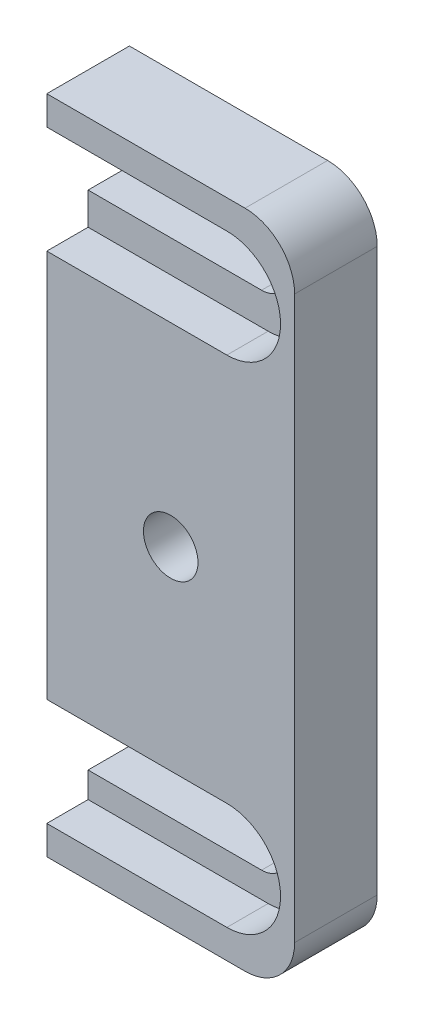
SolidWorks part; units mm, degrees
material "AISI 316 Annealed Stainless Steel Bar (SS)"
ref_plane "Front Plane" through (0, 0, 0) normal (0, 0, 1) x (1, 0, 0)
ref_plane "Top Plane" through (0, 0, 0) normal (0, 1, 0) x (1, 0, 0)
ref_plane "Right Plane" through (0, 0, 0) normal (1, 0, 0) x (0, 0, -1)
sketch "Sketch1" plane through (0, 0, 0) normal (0, 0, 1) x (1, 0, 0)
  line L0 (-7.5, 16.7) -> (3, 16.7)
  line L1 (-7.5, -20) -> (4.5, -20)
  line L2 (-7.5, -20) -> (-7.5, -16.7)
  line L3 (-7.5, 20) -> (4.5, 20)
  line L4 (7.5, -17) -> (7.5, 17)
  line L6 (-7.5, 20) -> (7.5, -20) construction
  line L7 (-7.5, 13.7) -> (3, 13.7)
  line L9 (-7.5, -13.7) -> (3, -13.7)
  line L10 (-7.5, -16.7) -> (3, -16.7)
  line L11 (-7.5, 16.7) -> (-7.5, 20)
  line L12 (-7.5, -13.7) -> (-7.5, 13.7)
  arc A0 (3, 13.7) -> (3, 16.7) centre (3, 15.2) ccw
  arc A1 (3, -13.7) -> (3, -16.7) centre (3, -15.2) cw
  arc A2 (7.5, -17) -> (4.5, -20) centre (4.5, -17) cw
  arc A3 (7.5, 17) -> (4.5, 20) centre (4.5, 17) ccw
  circle A4 centre (0, 0) radius 1.65
  point P0 (0, 0)
  dimension "D6" = 3
  dimension "D7" = 3.3
  dimension "D1" = 40
  dimension "D3" = 10.5
  dimension "D4" = 3.3
  dimension "D5" = 3.3
  dimension "D8" = 3
  dimension "D9" = 3
extrude "Boss-Extrude1" add sketch "Sketch1" along normal blind 5
sketch "Sketch2" plane through (0, 0, 5) normal (0, 0, 1) x (1, 0, 0)
  line L0 (-7.5, 20) -> (-7.5, 16.7) construction
  line L1 (-7.5, 18.25) -> (3.4, 18.25)
  line L2 (-7.5, 18.25) -> (-7.5, 11.75)
  line L3 (-7.5, 11.75) -> (3.4, 11.75)
  line L5 (4.5, 20) -> (-7.5, 20) construction
  line L6 (0, 0) -> (-6.2356, 0)
  line L7 (-7.5, -11.75) -> (3.4, -11.75)
  line L8 (-7.5, -18.25) -> (3.4, -18.25)
  line L9 (-7.5, -11.75) -> (-7.5, -18.25)
  arc A0 (3.4, 18.25) -> (3.4, 11.75) centre (3.4, 15) cw
  arc A1 (3.4, -18.25) -> (3.4, -11.75) centre (3.4, -15) ccw
  line M4 (-7.5, -16.7) -> (-7.5, -20)
  line M10 (-7.5, 20) -> (-7.5, 16.7)
  line M11 (-7.5, 16.7) -> (3, 16.7)
  arc M12 (3, 16.7) -> (3, 13.7) centre (3, 15.2) cw
  line M13 (3, 13.7) -> (-7.5, 13.7)
  line M14 (-7.5, 13.7) -> (-7.5, -13.7)
  line M15 (-7.5, -13.7) -> (3, -13.7)
  arc M16 (3, -13.7) -> (3, -16.7) centre (3, -15.2) cw
  line M17 (3, -16.7) -> (-7.5, -16.7)
  dimension "D1" = 10.9
  dimension "D2" = 6.5
  dimension "D3" = 1.75
extrude "Cut-Extrude1" cut sketch "Sketch2" against normal blind 2.5 contours L8 A1 L7 M14 M15 M16 M17 M4 | A0 L1 L3 M10 M11 M12 M13 M14
